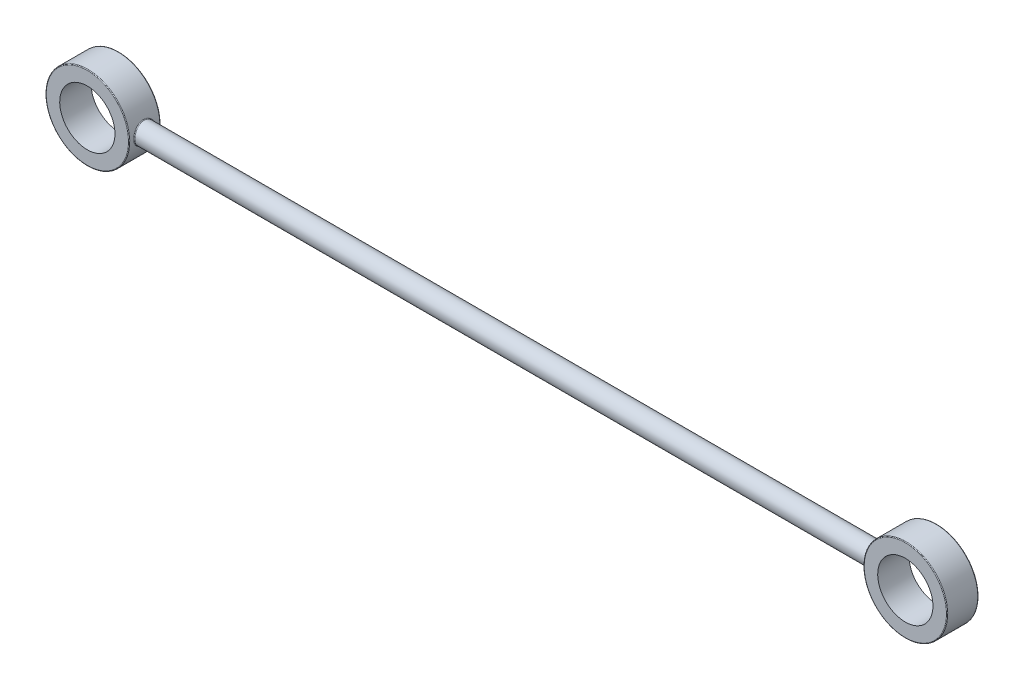
SolidWorks part; units mm, degrees
ref_plane "Front Plane" through (0, 0, 0) normal (0, 0, 1) x (1, 0, 0)
ref_plane "Top Plane" through (0, 0, 0) normal (0, 1, 0) x (1, 0, 0)
ref_plane "Right Plane" through (0, 0, 0) normal (1, 0, 0) x (0, 0, -1)
sketch "Sketch1" plane through (0, 0, 0) normal (0, 1, 0) x (1, 0, 0)
  line L0 (-126.16, 0) -> (-114.16, 0) construction
  line L1 (0, 0) -> (120.84, 0) construction
  line L4 (128.78, 0) -> (132.84, 0) construction
  circle A0 centre (-114.16, 0) radius 7.94
  circle A1 centre (120.84, 0) radius 7.94
  circle A2 centre (-114.16, 0) radius 12
  circle A3 centre (120.84, 0) radius 12
  point P1 (-114.16, 0)
  point P4 (120.84, 0)
  dimension "D2" = 15.88
  dimension "D3" = 24
  dimension "D1" = 235
extrude "Boss-Extrude1" add sketch "Sketch1" along normal mid plane 9
sketch "Sketch3" plane through (0, 0, 0) normal (1, 0, 0) x (0, 0, -1)
  circle A0 centre (0, 0) radius 3
  dimension "D1" = 6
extrude "Boss-Extrude2" add sketch "Sketch3" along normal up to next and the other way up to next
fillet "Fillet1" radius 0.2 6 edges at (-102.5262, -0.5876, 2.9419) (-114.16, 4.5, 12) (-114.16, -4.5, 12) (120.84, 4.5, 12) (120.84, -4.5, 12) (109.2062, 0.5876, -2.9419)
move or copy body "Body-Move/Copy2" bodies to move or copy 103 copy no rotation origin (0, 0, 0) rotation axis (1, 0, 0) rotation angle 90
